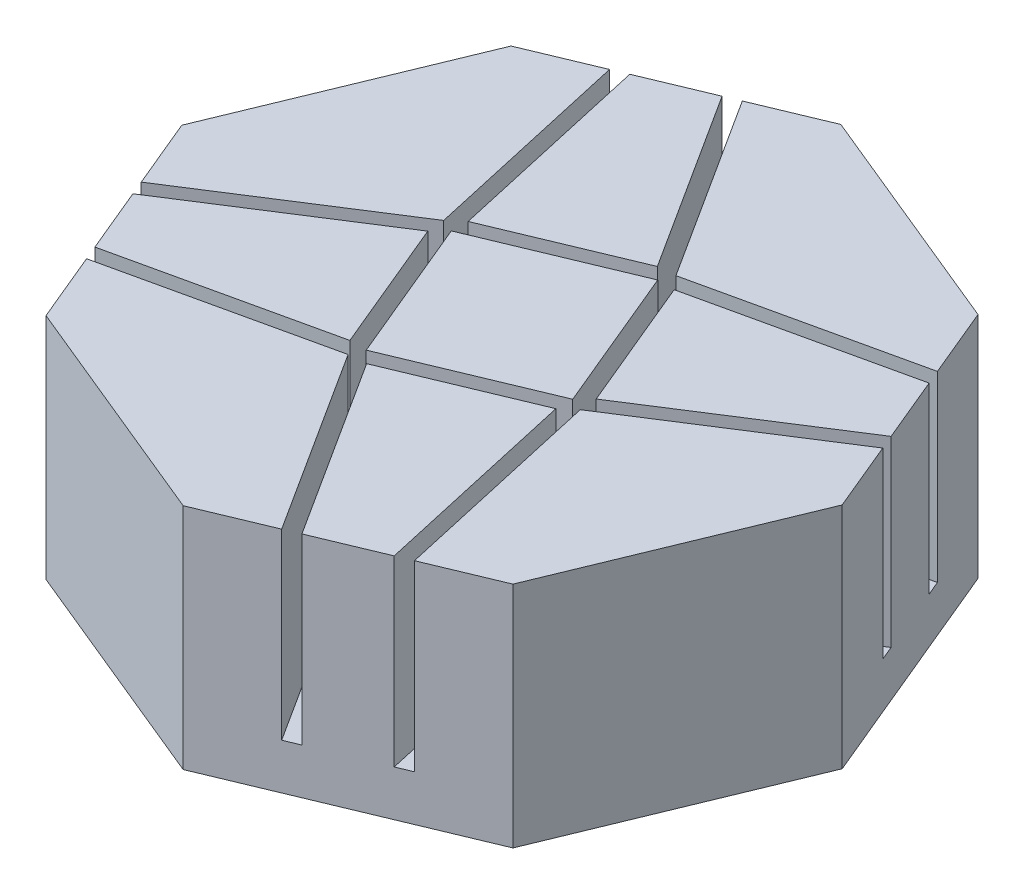
SolidWorks part; units mm, degrees
ref_plane "Front Plane" through (0, 0, 0) normal (0, 0, 1) x (1, 0, 0)
ref_plane "Top Plane" through (0, 0, 0) normal (0, 1, 0) x (1, 0, 0)
ref_plane "Right Plane" through (0, 0, 0) normal (1, 0, 0) x (0, 0, -1)
sketch "Sketch1" plane through (0, 0, 0) normal (0, 1, 0) x (1, 0, 0)
  line L1 (-0.112, 54.9379) -> (-38.9262, 38.7678)
  line L2 (-38.9262, 38.7678) -> (-54.9379, -0.112)
  line L3 (-54.9379, -0.112) -> (-38.7678, -38.9262)
  line L4 (-38.7678, -38.9262) -> (0.112, -54.9379)
  line L5 (0.112, -54.9379) -> (38.9262, -38.7678)
  line L6 (38.9262, -38.7678) -> (54.9379, 0.112)
  line L7 (54.9379, 0.112) -> (38.7678, 38.9262)
  line L8 (38.7678, 38.9262) -> (-0.112, 54.9379)
  circle A0 centre (0, 0) radius 50.7561 construction
  dimension "D2" = 101.5123
  dimension "D1" = 38.8798
  dimension "D3" = 42.0478
extrude "Boss-Extrude1" add sketch "Sketch1" along normal blind 38.1
sketch "Sketch2" plane through (0, 38.1, 0) normal (0, 1, 0) x (1, 0, 0)
  line L0 (19.5191, -46.8529) -> (6.0393, -14.4964) construction
  line L1 (-5.0979, -19.1362) -> (14.0872, -49.1158)
  line L2 (0.112, -54.9379) -> (38.9262, -38.7678) construction
  line L3 (17.1764, -9.8567) -> (24.9509, -44.5899)
  line L4 (-5.0979, -19.1362) -> (17.1764, -9.8567)
  line L5 (-19.1362, 5.0979) -> (-49.1158, -14.0872)
  line L6 (-19.1362, 5.0979) -> (-9.8567, -17.1764)
  line L7 (-9.8567, -17.1764) -> (-44.5899, -24.9509)
  line L8 (-46.8529, -19.5191) -> (-14.4964, -6.0393) construction
  line L9 (5.0979, 19.1362) -> (-14.0872, 49.1158)
  line L10 (5.0979, 19.1362) -> (-17.1764, 9.8567)
  line L11 (-17.1764, 9.8567) -> (-24.9509, 44.5899)
  line L12 (-19.5191, 46.8529) -> (-6.0393, 14.4964) construction
  line L13 (19.1362, -5.0979) -> (49.1158, 14.0872)
  line L14 (19.1362, -5.0979) -> (9.8567, 17.1764)
  line L15 (9.8567, 17.1764) -> (44.5899, 24.9509)
  line L16 (46.8529, 19.5191) -> (14.4964, 6.0393) construction
  point P30 (0, 0)
  dimension "D1" = 14.4964
  dimension "D2" = 24.13
  dimension "D3" = 35.052
  dimension "D4" = 80
  dimension "D5" = 80
  dimension "D6" = 4
  dimension "D7" = 14.4964
  dimension "D8" = 5.1465
extrude "Cut-Extrude-Thin1" cut sketch "Sketch2" against normal blind 30.48 thin
